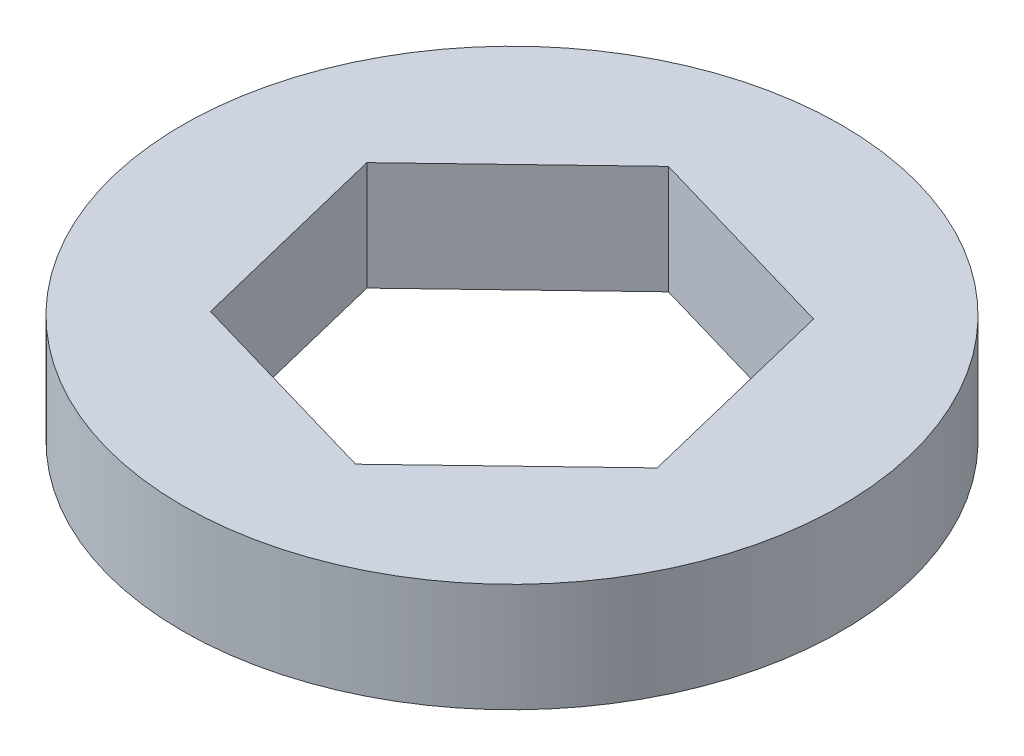
SolidWorks part; units mm, degrees
ref_plane "Front" through (0, 0, 0) normal (0, 0, 1) x (1, 0, 0)
ref_plane "Top" through (0, 0, 0) normal (0, 1, 0) x (1, 0, 0)
ref_plane "Right" through (0, 0, 0) normal (1, 0, 0) x (0, 0, -1)
sketch "Sketch1" plane through (0, 0, 0) normal (0, 1, 0) x (1, 0, 0)
  circle A0 centre (0, 0) radius 4.55
extrude "Boss-Extrude1" add sketch "Sketch1" along normal blind 1.5
sketch "Sketch2" plane through (0, 1.5, 0) normal (0, 1, 0) x (1, 0, 0)
  line L1 (-2.1264, -2.0368) -> (0.7008, -2.8599)
  line L2 (0.7008, -2.8599) -> (2.8271, -0.8231)
  line L3 (2.8271, -0.8231) -> (2.1264, 2.0368)
  line L4 (2.1264, 2.0368) -> (-0.7008, 2.8599)
  line L5 (-0.7008, 2.8599) -> (-2.8271, 0.8231)
  line L6 (-2.8271, 0.8231) -> (-2.1264, -2.0368)
  circle A0 centre (0, 0) radius 2.55 construction
  dimension "D1" = 5.1
extrude "Cut-Extrude1" cut sketch "Sketch2" against normal blind 15
